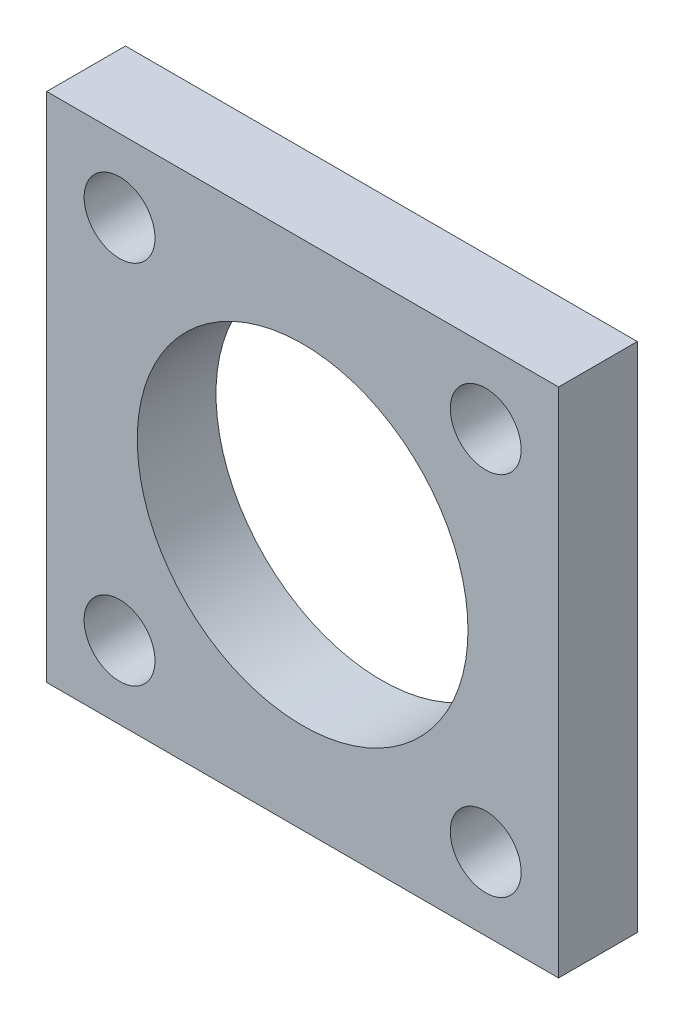
SolidWorks part; units mm, degrees
ref_plane "Płaszczyzna przednia" through (0, 0, 0) normal (0, 0, 1) x (1, 0, 0)
ref_plane "Płaszczyzna górna" through (0, 0, 0) normal (0, 1, 0) x (1, 0, 0)
ref_plane "Płaszczyzna prawa" through (0, 0, 0) normal (1, 0, 0) x (0, 0, -1)
sketch "Szkic1" plane through (0, 0, 0) normal (0, 0, 1) x (1, 0, 0)
  line L1 (-23.25, 23.25) -> (23.25, 23.25) construction
  line L2 (-23.25, 23.25) -> (-23.25, -23.25) construction
  line L3 (-23.25, -23.25) -> (23.25, -23.25) construction
  line L4 (23.25, 23.25) -> (23.25, -23.25) construction
  line L5 (-23.25, 23.25) -> (23.25, -23.25) construction
  line L6 (-23.25, -23.25) -> (23.25, 23.25) construction
  line L7 (-32.5, 32.5) -> (32.5, 32.5)
  line L8 (-32.5, 32.5) -> (-32.5, -32.5)
  line L9 (-32.5, -32.5) -> (32.5, -32.5)
  line L10 (32.5, 32.5) -> (32.5, -32.5)
  line L11 (-32.5, 32.5) -> (32.5, -32.5) construction
  line L12 (-32.5, -32.5) -> (32.5, 32.5) construction
  circle A1 centre (0, 0) radius 21
  circle A5 centre (-23.25, 23.25) radius 4.5
  circle A6 centre (23.25, 23.25) radius 4.5
  circle A7 centre (23.25, -23.25) radius 4.5
  circle A8 centre (-23.25, -23.25) radius 4.5
  point P0 (0, 0)
  dimension "D3" = 42
  dimension "D4" = 9
  dimension "D1" = 46.5
  dimension "D2" = 46.5
  dimension "D6" = 65
  dimension "D7" = 65
  dimension "D5" = 2
  dimension "D8" = 2
extrude "Dodanie-wyciągnięcie1" add sketch "Szkic1" along normal blind 10
